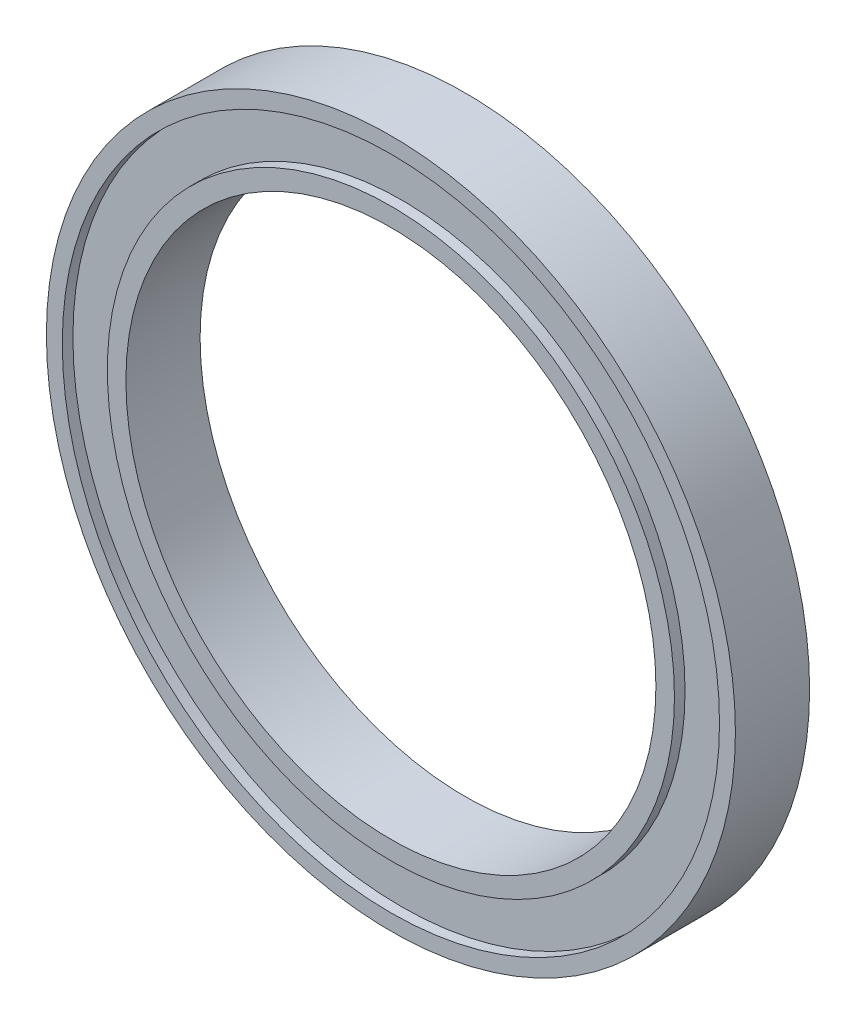
SolidWorks part; units mm, degrees
ref_plane "Front Plane" through (0, 0, 0) normal (0, 0, 1) x (1, 0, 0)
ref_plane "Top Plane" through (0, 0, 0) normal (0, 1, 0) x (1, 0, 0)
ref_plane "Right Plane" through (0, 0, 0) normal (1, 0, 0) x (0, 0, -1)
sketch "Sketch1" plane through (0, 0, 0) normal (0, 0, 1) x (1, 0, 0)
  circle A0 centre (0, 0) radius 32.5
  circle A1 centre (0, 0) radius 25
  dimension "D1" = 65
  dimension "D2" = 50
extrude "Boss-Extrude1" add sketch "Sketch1" along normal mid plane 7
sketch "Sketch2" plane through (0, 0, 3.5) normal (0, 0, 1) x (1, 0, 0)
  circle A0 centre (0, 0) radius 31
  circle A1 centre (0, 0) radius 26.75
  dimension "D1" = 53.5
  dimension "D2" = 62
extrude "Cut-Extrude1" cut sketch "Sketch2" against normal blind 1
mirror "Mirror1" about plane through (0, 0, 0) normal (0, 0, 1) of "Cut-Extrude1"
